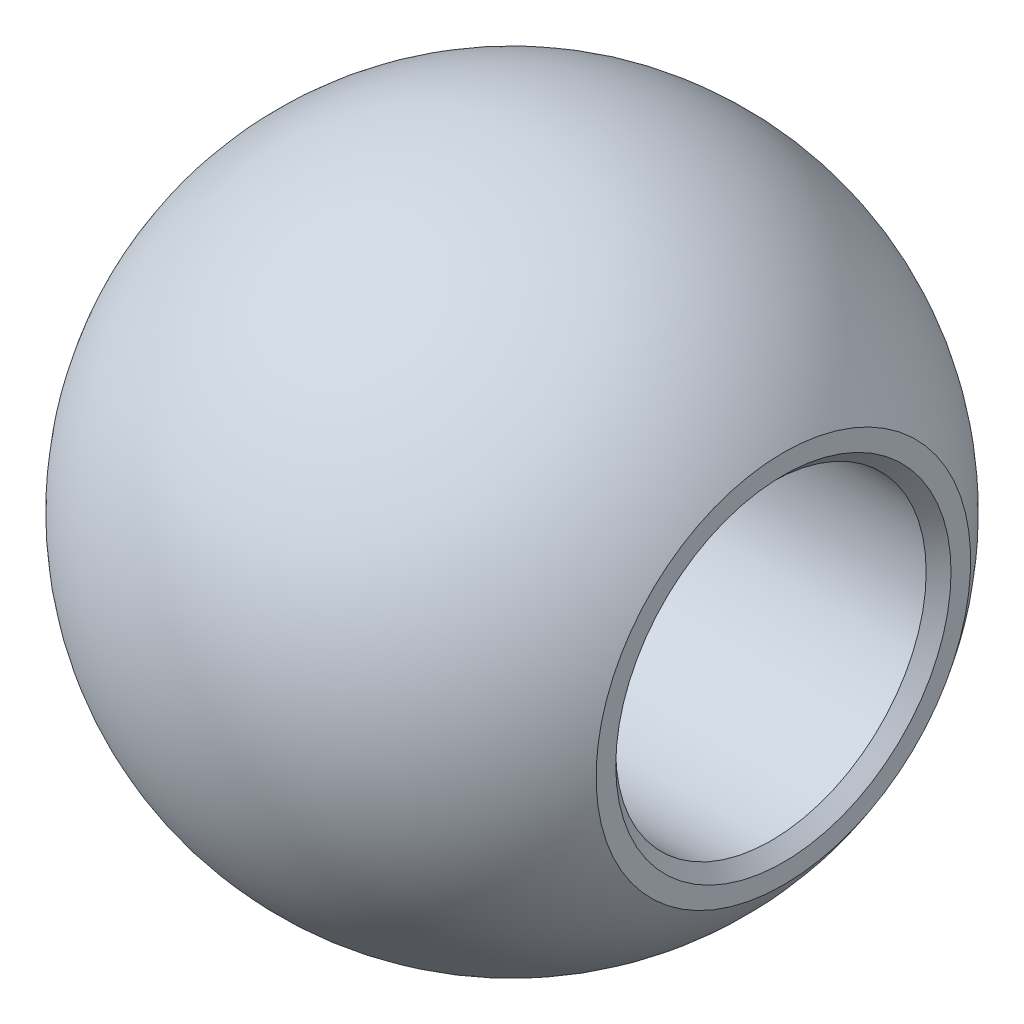
SolidWorks part; units mm, degrees
material "AISI 316 Annealed Stainless Steel Bar (SS)"
ref_plane "Front Plane" through (0, 0, 0) normal (0, 0, 1) x (1, 0, 0)
ref_plane "Top Plane" through (0, 0, 0) normal (0, 1, 0) x (1, 0, 0)
ref_plane "Right Plane" through (0, 0, 0) normal (1, 0, 0) x (0, 0, -1)
sketch "Sketch1" plane through (0, 0, 0) normal (0, 0, 1) x (1, 0, 0)
  line L0 (-6.8851, 0) -> (-3.8904, 0) construction
  line L1 (-5.5499, 3.8309) -> (-5.5499, 3.175)
  line L2 (-5.5499, 3.175) -> (5.5499, 3.175)
  line L3 (5.5499, 3.175) -> (5.5499, 3.8309)
  arc A0 (5.5499, 3.8309) -> (-5.5499, 3.8309) centre (0, 0) ccw
  dimension "Ball_Dia" = 13.4874
  dimension "B" = 6.35
  dimension "W" = 11.0998
revolve "Revolve1" add sketch "Sketch1" angle 360 about L0
chamfer "Chamfer1" distance 0.254 angle 45 2 edges at (-5.5499, 0, 3.175) (5.5499, 0, 3.175)
